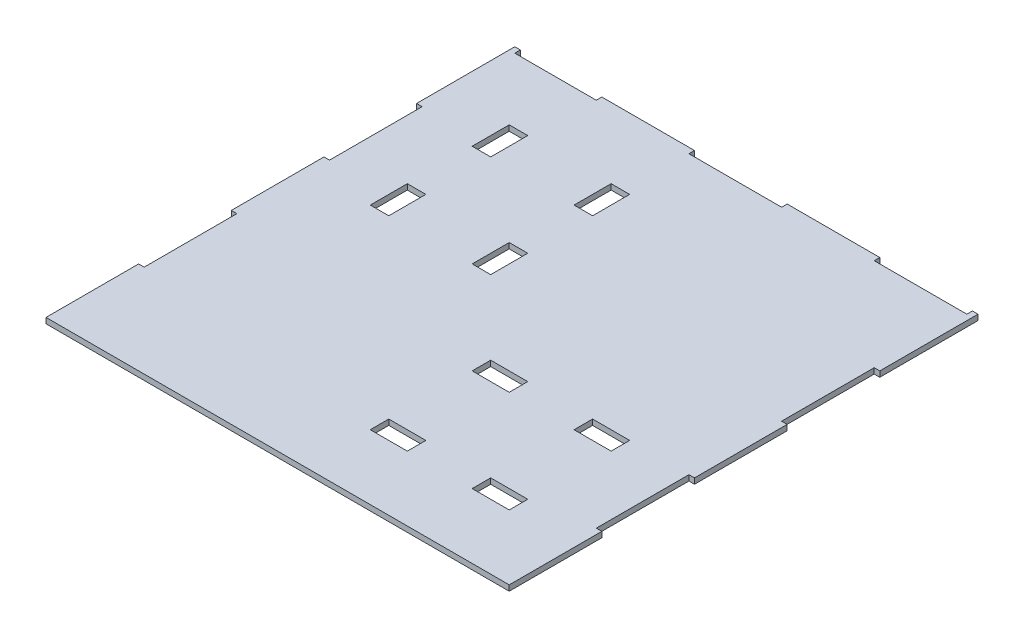
SolidWorks part; units mm, degrees
ref_plane "Front Plane" through (0, 0, 0) normal (0, 0, 1) x (1, 0, 0)
ref_plane "Top Plane" through (0, 0, 0) normal (0, 1, 0) x (1, 0, 0)
ref_plane "Right Plane" through (0, 0, 0) normal (1, 0, 0) x (0, 0, -1)
sketch "Sketch1" plane through (0, 0, 0) normal (0, 1, 0) x (1, 0, 0)
  line L0 (250, 100) -> (250, 150)
  line L1 (0, 0) -> (250, 0)
  line L2 (0, 0) -> (0, 50)
  line L3 (3, 250) -> (47, 250)
  line L4 (250, 0) -> (250, 50)
  line L5 (0, 200) -> (0, 250)
  line L6 (47, 250) -> (47, 253)
  line L7 (47, 253) -> (97, 253)
  line L8 (97, 250) -> (97, 253)
  line L9 (250, 200) -> (247, 200)
  line L10 (197, 250) -> (247, 250)
  line L11 (250, 150) -> (247, 150)
  line L12 (247, 200) -> (247, 150)
  line L14 (90, 160) -> (100, 160)
  line L15 (90, 160) -> (90, 140)
  line L16 (45, 140) -> (35, 140)
  line L17 (0, 200) -> (3, 200)
  line L18 (0, 100) -> (0, 150)
  line L19 (0, 150) -> (3, 150)
  line L20 (3, 200) -> (3, 150)
  line L21 (45, 140) -> (45, 160)
  line L22 (45, 160) -> (35, 160)
  line L23 (35, 140) -> (35, 160)
  line L24 (90, 140) -> (100, 140)
  line L25 (97, 250) -> (147, 250)
  line L26 (147, 250) -> (147, 253)
  line L27 (147, 253) -> (197, 253)
  line L28 (197, 250) -> (197, 253)
  line L29 (250, 100) -> (247, 100)
  line L30 (250, 200) -> (250, 250)
  line L31 (250, 50) -> (247, 50)
  line L32 (247, 100) -> (247, 50)
  line L33 (0, 100) -> (3, 100)
  line L34 (100, 160) -> (100, 140)
  line L35 (0, 50) -> (3, 50)
  line L36 (3, 100) -> (3, 50)
  line L37 (195, 100) -> (215, 100)
  line L38 (195, 100) -> (195, 90)
  line L39 (195, 90) -> (215, 90)
  line L40 (215, 100) -> (215, 90)
  line L41 (195, 45) -> (215, 45)
  line L42 (195, 45) -> (195, 35)
  line L43 (195, 35) -> (215, 35)
  line L44 (215, 45) -> (215, 35)
  line L45 (35, 215) -> (45, 215)
  line L46 (35, 215) -> (35, 195)
  line L47 (35, 195) -> (45, 195)
  line L48 (45, 215) -> (45, 195)
  line L49 (90, 215) -> (100, 215)
  line L50 (90, 215) -> (90, 195)
  line L51 (90, 195) -> (100, 195)
  line L52 (100, 215) -> (100, 195)
  line L53 (140, 100) -> (160, 100)
  line L54 (140, 100) -> (140, 90)
  line L55 (140, 90) -> (160, 90)
  line L56 (160, 100) -> (160, 90)
  line L57 (140, 45) -> (160, 45)
  line L58 (140, 45) -> (140, 35)
  line L59 (140, 35) -> (160, 35)
  line L60 (160, 45) -> (160, 35)
  line L62 (250, 250) -> (250, 253)
  line L63 (250, 253) -> (247, 253)
  line L64 (247, 250) -> (247, 253)
  line L65 (0, 250) -> (0, 253)
  line L66 (0, 253) -> (3, 253)
  line L67 (3, 250) -> (3, 253)
  dimension "D1" = 250
  dimension "D2" = 250
  dimension "D3" = 50
  dimension "D4" = 3
  dimension "D5" = 10
  dimension "D6" = 20
  dimension "D7" = 35
  dimension "D8" = 35
  dimension "D9" = 45
  dimension "D10" = 45
  dimension "D11" = 35
  dimension "D12" = 35
  dimension "D13" = 35
  dimension "D14" = 35
  dimension "D15" = 35
  dimension "D16" = 35
  dimension "D17" = 35
  dimension "D18" = 35
  dimension "D19" = 50
  dimension "D20" = 45
  dimension "D21" = 45
  dimension "D22" = 35
  dimension "D23" = 35
  dimension "D24" = 50
  dimension "D25" = 50
  dimension "D26" = 50
  dimension "D27" = 50
  dimension "D28" = 53
  dimension "D29" = 50
  dimension "D30" = 50
  dimension "D31" = 50
  dimension "D32" = 47
  dimension "D33" = 3
  dimension "D34" = 50
  dimension "D35" = 50
  dimension "D36" = 50
  dimension "D37" = 47
  dimension "D38" = 50
  dimension "D39" = 3
  dimension "D40" = 3
  dimension "D41" = 3
  dimension "D42" = 3
  dimension "D43" = 3
extrude "Boss-Extrude1" add sketch "Sketch1" along normal blind 3
equation "\"w\"=3"
equation "\"L\"=50"
